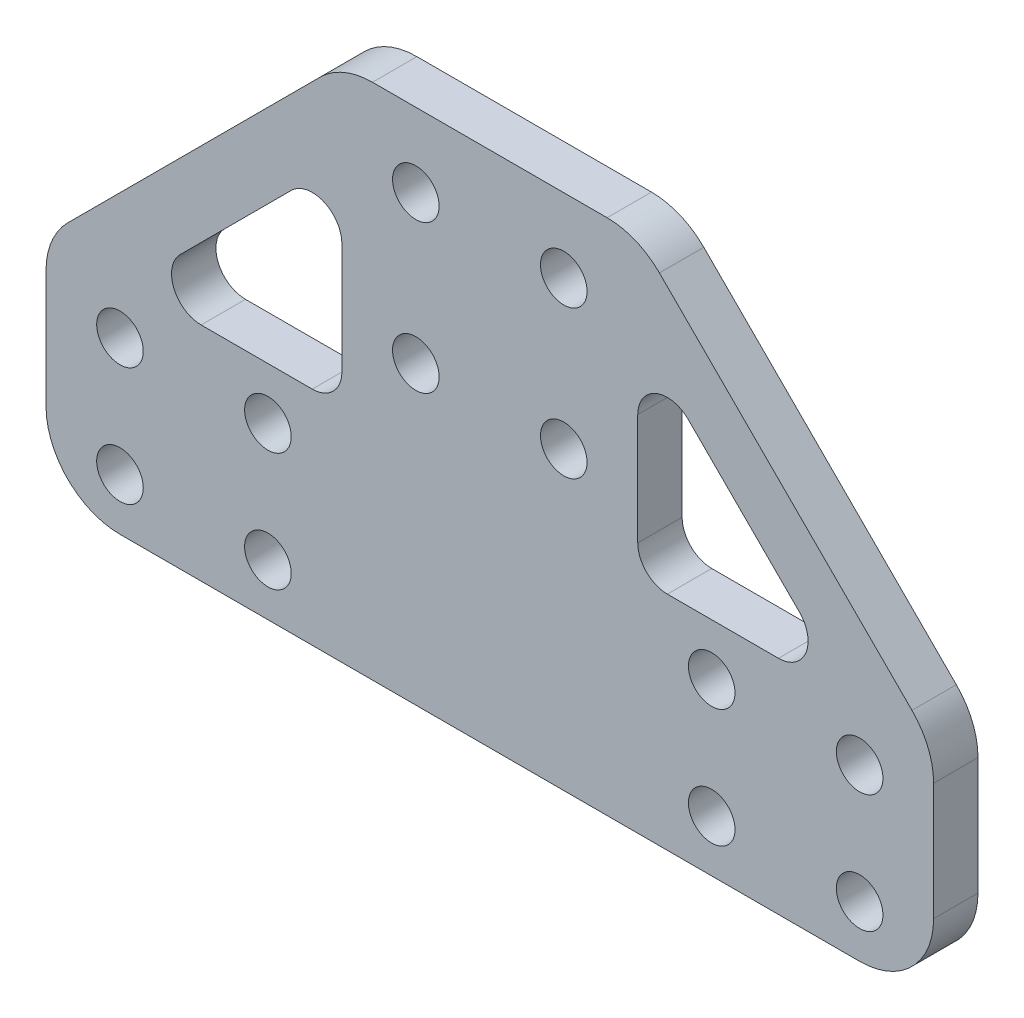
SolidWorks part; units mm, degrees
ref_plane "前视基准面" through (0, 0, 0) normal (0, 0, 1) x (1, 0, 0)
ref_plane "上视基准面" through (0, 0, 0) normal (0, 1, 0) x (1, 0, 0)
ref_plane "右视基准面" through (0, 0, 0) normal (1, 0, 0) x (0, 0, -1)
other "Configuration Table"
sketch "草图1" plane through (0, 0, 0) normal (0, 0, 1) x (1, 0, 0)
  line L0 (0, 0) -> (20, 0)
  line L1 (20, 0) -> (40, -20)
  line L2 (40, -20) -> (40, -35)
  line L3 (40, -35) -> (-20, -35)
  line L4 (-20, -35) -> (-20, -20)
  line L5 (-20, -20) -> (0, 0)
  line L6 (10, 0) -> (10, -35) construction
  dimension "D1" = 20
  dimension "D2" = 15
  dimension "D3" = 60
  dimension "D4" = 45
extrude "凸台-拉伸1" add sketch "草图1" along normal blind 3
sketch "草图2" plane through (0, 0, 3) normal (0, 0, 1) x (1, 0, 0)
  line L0 (10, 0) -> (10, -35) construction
  line L1 (20, 0) -> (0, 0) construction
  line L2 (-20, -35) -> (40, -35) construction
  line L3 (-10, -10) -> (30, -10) construction
  line L4 (0, 0) -> (-20, -20) construction
  line L5 (40, -20) -> (20, 0) construction
  line L6 (-20, -27.5) -> (10, -27.5) construction
  line L7 (-20, -20) -> (-20, -35) construction
  line L8 (-10, -35) -> (-10, -27.5) construction
  line L9 (0, -5.6569) -> (0, -20)
  line L10 (0, -20) -> (-14.3431, -20)
  line L11 (-14.3431, -20) -> (0, -5.6569)
  line L12 (34.3431, -20) -> (20, -5.6569)
  line L13 (20, -20) -> (34.3431, -20)
  line L14 (20, -5.6569) -> (20, -20)
  circle A0 centre (5, -5) radius 1.575
  circle A1 centre (15, -5) radius 1.575
  circle A2 centre (15, -15) radius 1.575
  circle A3 centre (5, -15) radius 1.575
  circle A4 centre (-15, -31.5) radius 1.575
  circle A5 centre (-15, -23.5) radius 1.575
  circle A6 centre (-5, -31.5) radius 1.575
  circle A7 centre (-5, -23.5) radius 1.575
  circle A8 centre (25, -31.5) radius 1.575
  circle A9 centre (35, -31.5) radius 1.575
  circle A10 centre (25, -23.5) radius 1.575
  circle A11 centre (35, -23.5) radius 1.575
  dimension "D3" = 3.15
  dimension "D5" = 3.15
  dimension "D1" = 5
  dimension "D2" = 5
  dimension "D4" = 20
  dimension "D6" = 5
  dimension "D7" = 4
  dimension "D8" = 4
extrude "切除-拉伸1" cut sketch "草图2" against normal through all
fillet "圆角1" radius 2 6 edges at (20, -20, 1.5) (34.3431, -20, 1.5) (20, -5.6569, 1.5) (0, -20, 1.5) (0, -5.6569, 1.5) (-14.3431, -20, 1.5)
fillet "圆角2" radius 5 6 edges at (40, -35, 1.5) (40, -20, 1.5) (-20, -35, 1.5) (-20, -20, 1.5) (20, 0, 1.5) (0, 0, 1.5)
